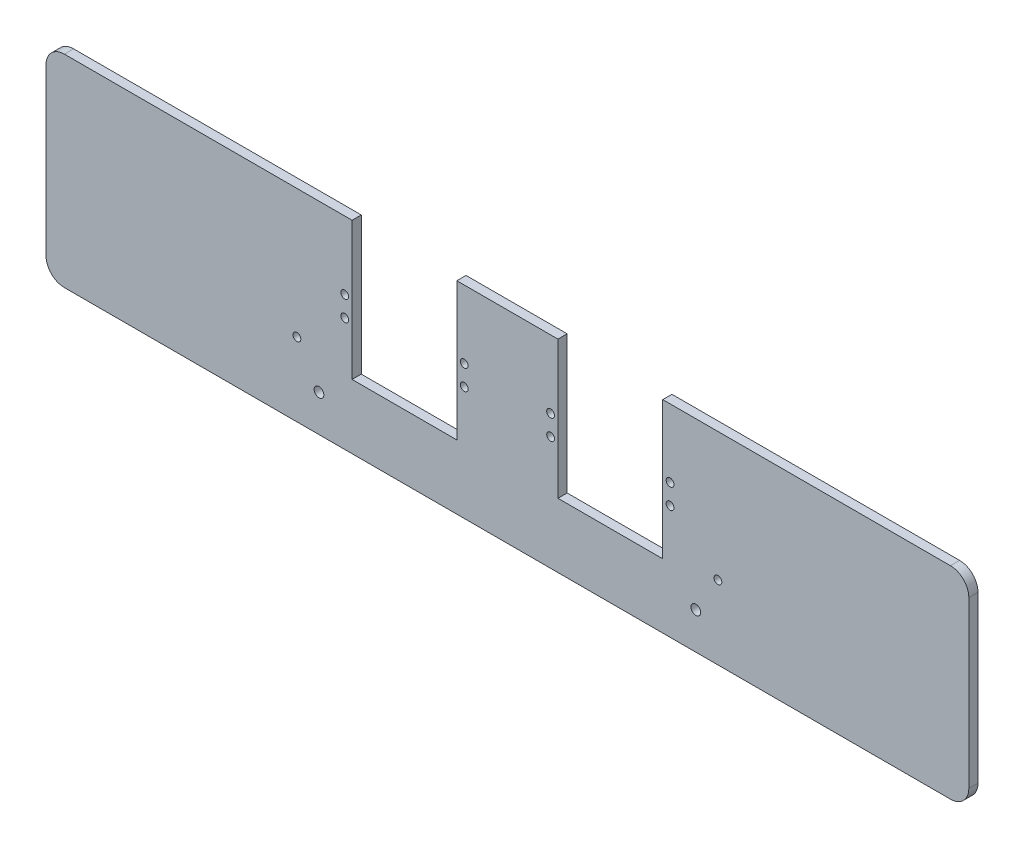
SolidWorks part; units mm, degrees
ref_plane "Front Plane" through (0, 0, 0) normal (0, 0, 1) x (1, 0, 0)
ref_plane "Top Plane" through (0, 0, 0) normal (0, 1, 0) x (1, 0, 0)
ref_plane "Right Plane" through (0, 0, 0) normal (1, 0, 0) x (0, 0, -1)
sketch "Sketch1" plane through (0, 0, 0) normal (0, 0, 1) x (1, 0, 0)
  line L0 (0, 0) -> (0, 110)
  line L1 (0, 110) -> (166.5, 110)
  line L2 (166.5, 110) -> (166.5, 35)
  line L3 (166.5, 35) -> (223.5, 35)
  line L4 (223.5, 35) -> (223.5, 110)
  line L5 (223.5, 110) -> (278.5, 110)
  line L6 (278.5, 110) -> (278.5, 35)
  line L7 (278.5, 35) -> (335.5, 35)
  line L8 (335.5, 35) -> (335.5, 110)
  line L9 (335.5, 110) -> (502, 110)
  line L10 (502, 110) -> (502, 0)
  line L11 (502, 0) -> (0, 0)
  dimension "D1" = 166.5
  dimension "D2" = 57
  dimension "D3" = 55
  dimension "D4" = 57
  dimension "124" = 166.5
  dimension "D6" = 110
  dimension "D7" = 75
  dimension "D8" = 75
  dimension "D9" = 75
  dimension "D10" = 75
extrude "Boss-Extrude1" add sketch "Sketch1" along normal blind 5
sketch "Sketch3" plane through (0, 0, 5) normal (0, 0, 1) x (1, 0, 0)
  line L0 (195, 35) -> (195, 133.0594) construction
  line L1 (223.5, 35) -> (166.5, 35) construction
  line L2 (251, 110) -> (251, 1.7727) construction
  line L3 (278.5, 110) -> (223.5, 110) construction
  line L4 (166.5, 35) -> (166.5, 110) construction
  circle A0 centre (162.5, 73) radius 2.125
  circle A1 centre (162.5, 62) radius 2.125
  circle A2 centre (227.5, 62) radius 2.125
  circle A3 centre (227.5, 73) radius 2.125
  circle A4 centre (274.5, 73) radius 2.125
  circle A5 centre (274.5, 62) radius 2.125
  circle A6 centre (339.5, 62) radius 2.125
  circle A7 centre (339.5, 73) radius 2.125
  dimension "D1" = 4.25
  dimension "D2" = 4.25
  dimension "D3" = 27
  dimension "D4" = 38
  dimension "D5" = 4
  dimension "D6" = 4
extrude "Cut-Extrude1" cut sketch "Sketch3" against normal blind 10
fillet "Fillet1" radius 10 4 edges at (502, 0, 2.5) (502, 110, 2.5) (0, 0, 2.5) (0, 110, 2.5)
sketch "Sketch4" plane through (0, 0, 5) normal (0, 0, 1) x (1, 0, 0)
  line L0 (166.5, 35) -> (166.5, 110) construction
  line L1 (10, 0) -> (492, 0) construction
  line L2 (251, 110) -> (251, 0) construction
  line L3 (278.5, 110) -> (223.5, 110) construction
  line L4 (0, 100) -> (0, 10) construction
  circle A1 centre (148.5, 20) radius 2.65
  circle A2 centre (353.5, 20) radius 2.65
  dimension "D3" = 5.3
  dimension "D1" = 18
  dimension "D2" = 20
extrude "Cut-Extrude2" cut sketch "Sketch4" against normal blind 10
sketch "Sketch5" plane through (0, 0, 5) normal (0, 0, 1) x (1, 0, 0)
  line L0 (10, 0) -> (492, 0) construction
  line L1 (335.5, 110) -> (335.5, 35) construction
  line L2 (251, 110) -> (251, 0) construction
  line L3 (278.5, 110) -> (223.5, 110) construction
  line L4 (502, 10) -> (502, 100) construction
  circle A0 centre (365.5, 40) radius 2.125
  circle A1 centre (136.5, 40) radius 2.125
  dimension "D1" = 4.25
  dimension "D2" = 40
  dimension "D3" = 30
extrude "Cut-Extrude3" cut sketch "Sketch5" against normal blind 10
